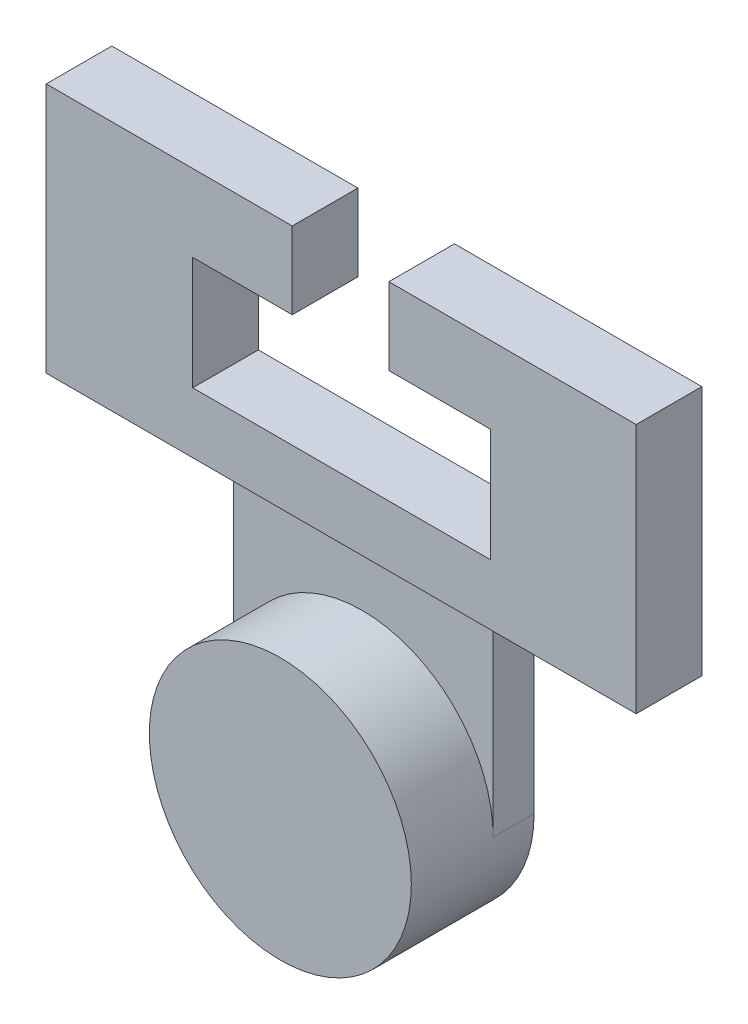
SolidWorks part; units mm, degrees
ref_plane "Front Plane" through (0, 0, 0) normal (0, 0, 1) x (1, 0, 0)
ref_plane "Top Plane" through (0, 0, 0) normal (0, 1, 0) x (1, 0, 0)
ref_plane "Right Plane" through (0, 0, 0) normal (1, 0, 0) x (0, 0, -1)
sketch "Sketch1" plane through (0, 0, 0) normal (0, 0, 1) x (1, 0, 0)
  circle A0 centre (0, 0) radius 10.16
  point P3 (0, 0)
  dimension "D1" = 20.32
extrude "Boss-Extrude1" add sketch "Sketch1" against normal blind 9.525
sketch "Sketch2" plane through (0, 0, -9.525) normal (0, 0, -1) x (-1, 0, 0)
  line L1 (-10.16, 0) -> (9.9915, 0)
  line L2 (-10.16, 0) -> (-10.16, 15.7545)
  line L3 (-10.16, 15.7545) -> (9.9915, 15.7545)
  line L4 (9.9915, 0) -> (9.9915, 15.7545)
  circle A0 centre (0, 0) radius 10.16 construction
extrude "Boss-Extrude4" add sketch "Sketch2" against normal blind 3.175
sketch "Sketch3" plane through (0, 15.7545, 0) normal (0, 1, 0) x (1, 0, 0)
  line L0 (-9.9915, 9.525) -> (-22.594, 9.525)
  line L1 (-22.594, 9.525) -> (-22.594, 4.4351)
  line L2 (-22.594, 4.4351) -> (23.1661, 4.4351)
  line L3 (23.1661, 4.4351) -> (23.1661, 9.525)
  line L4 (23.1661, 9.525) -> (-9.9915, 9.525)
extrude "Boss-Extrude5" add sketch "Sketch3" along normal blind 4.699
sketch "Sketch4" plane through (0, 20.4535, 0) normal (0, 1, 0) x (1, 0, 0)
  line L0 (-22.594, 4.4351) -> (23.1661, 4.4351) construction
  line L1 (-22.594, 9.525) -> (-11.2293, 9.525)
  line L2 (-22.594, 9.525) -> (-22.594, 4.4351)
  line L3 (-22.594, 4.4351) -> (-11.2293, 4.4351)
  line L4 (-11.2293, 9.525) -> (-11.2293, 4.4351)
  line L5 (23.1661, 9.525) -> (-22.594, 9.525) construction
  line L6 (23.1661, 9.525) -> (11.852, 9.525)
  line L7 (23.1661, 9.525) -> (23.1661, 4.4351)
  line L8 (23.1661, 4.4351) -> (11.852, 4.4351)
  line L9 (11.852, 9.525) -> (11.852, 4.4351)
extrude "Boss-Extrude6" add sketch "Sketch4" along normal blind 8.763
sketch "Sketch5" plane through (0, 29.2165, 0) normal (0, 1, 0) x (1, 0, 0)
  line L0 (-11.2293, 4.4351) -> (11.852, 4.4351) construction
  line L1 (-22.594, 9.525) -> (-3.5102, 9.525)
  line L2 (-22.594, 9.525) -> (-22.594, 4.4351)
  line L3 (-22.594, 4.4351) -> (-3.5102, 4.4351)
  line L4 (-3.5102, 9.525) -> (-3.5102, 4.4351)
  line L6 (23.1661, 9.525) -> (3.9811, 9.525)
  line L7 (23.1661, 9.525) -> (23.1661, 4.4351)
  line L8 (23.1661, 4.4351) -> (3.9811, 4.4351)
  line L9 (3.9811, 9.525) -> (3.9811, 4.4351)
extrude "Boss-Extrude7" add sketch "Sketch5" along normal blind 5.969
